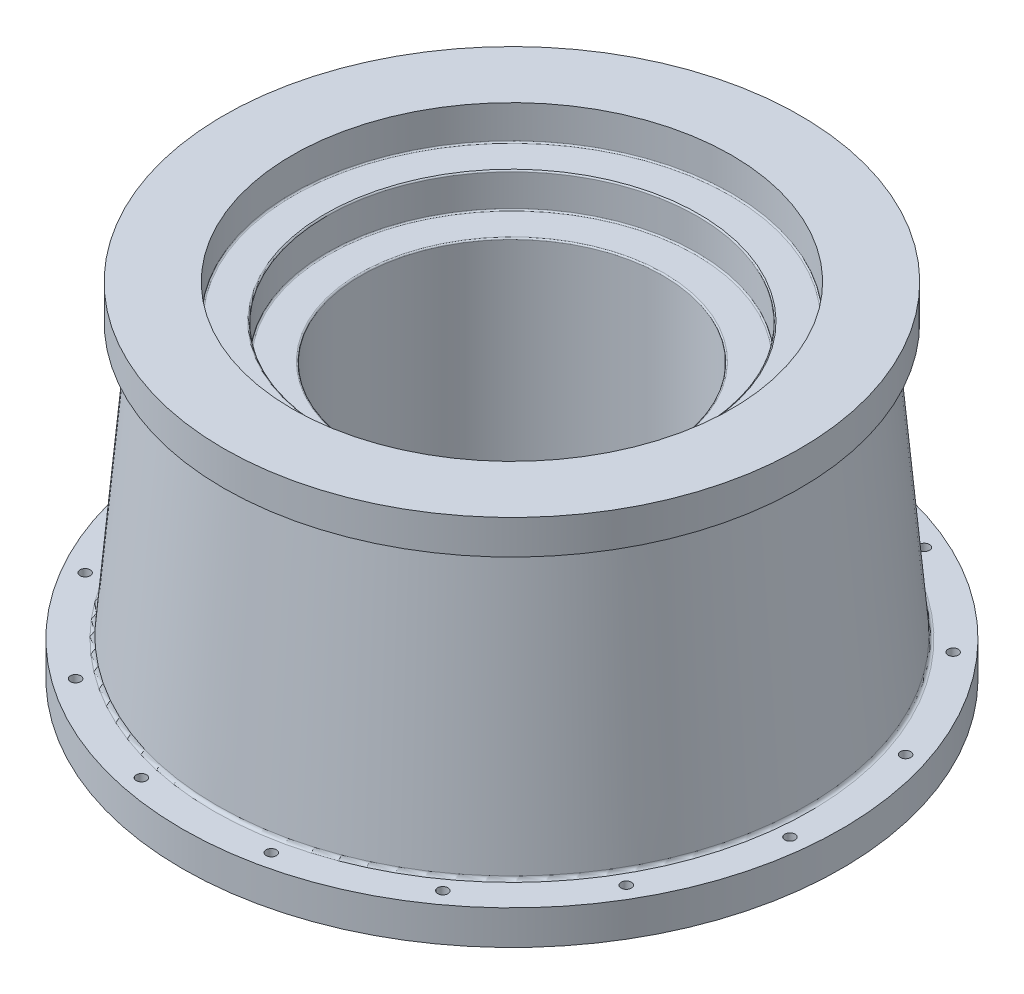
SolidWorks part; units mm, degrees
material "Structural Steel"
ref_plane "Front Plane" through (0, 0, 0) normal (0, 0, 1) x (1, 0, 0)
ref_plane "Top Plane" through (0, 0, 0) normal (0, 1, 0) x (1, 0, 0)
ref_plane "Right Plane" through (0, 0, 0) normal (1, 0, 0) x (0, 0, -1)
sketch "Sketch2" plane through (0, 0, 0) normal (0, 0, 1) x (1, 0, 0)
  line L0 (0, 634.3138) -> (0, 0) construction
  line L1 (-220, 0) -> (-479.9955, 0)
  line L2 (-479.9955, 0) -> (-479.9955, 50)
  line L3 (-479.9955, 50) -> (-429.9955, 50)
  line L4 (-429.9955, 50) -> (-395, 450)
  line L5 (-395, 450) -> (-420, 450)
  line L6 (-420, 450) -> (-420, 500)
  line L7 (-420, 500) -> (-320, 500)
  line L8 (-320, 500) -> (-320, 450)
  line L9 (-320, 450) -> (-270, 450)
  line L10 (-270, 450) -> (-270, 400)
  line L11 (-270, 400) -> (-220, 400)
  line L12 (-220, 400) -> (-220, 0)
  line L13 (-395, 450) -> (-395, -141.8562) construction
  dimension "D1" = 50
  dimension "D2" = 50
  dimension "D3" = 500
  dimension "D4" = 50
  dimension "D5" = 100
  dimension "D6" = 25
  dimension "D7" = 50
  dimension "D8" = 50
  dimension "D9" = 50
  dimension "D10" = 50
  dimension "D11" = 320
  dimension "D12" = 5
revolve "Revolve1" add sketch "Sketch2" angle 360 about L0
sketch "Sketch3" plane through (0, 50, 0) normal (0, 1, 0) x (1, 0, 0)
  circle A0 centre (0, 454.9955) radius 7.5
  circle A1 centre (0, 0) radius 454.9955 construction
  circle A2 centre (0, 0) radius 479.9955 construction
  dimension "D1" = 15
  dimension "D2" = 25
extrude "Cut-Extrude1" cut sketch "Sketch3" against normal through all
pattern_circular "CirPattern1" count 15 over 360 about axis through (0, 0, 0) along (0, 1, 0) of "Cut-Extrude1"
fillet "Fillet1" radius 2 4 edges at (0, 400, 270) (0, 450, 320) (0, 400, 220) (0, 450, 270)
fillet "Fillet2" radius 5 2 edges at (0, 50, 429.9955) (0, 450, 395)
sketch "Sketch4" plane through (0, 500, 0) normal (0, 1, 0) x (1, 0, 0)
  line L0 (-829.4074, 0) -> (892.6673, 0) construction
  point P3 (0, 0)
ref_plane "mesh_plane1" [suppressed] through (0, 452, 0) normal (0, 1, 0) x (1, 0, 0)
ref_plane "mesh_plane2" [suppressed] through (0, 402, 0) normal (0, -1, 0) x (-1, 0, 0)
ref_plane "mesh_plane3" [suppressed] through (0, 398, 0) normal (0, -1, 0) x (-1, 0, 0)
split "Split1" [suppressed] bodies to split 103
